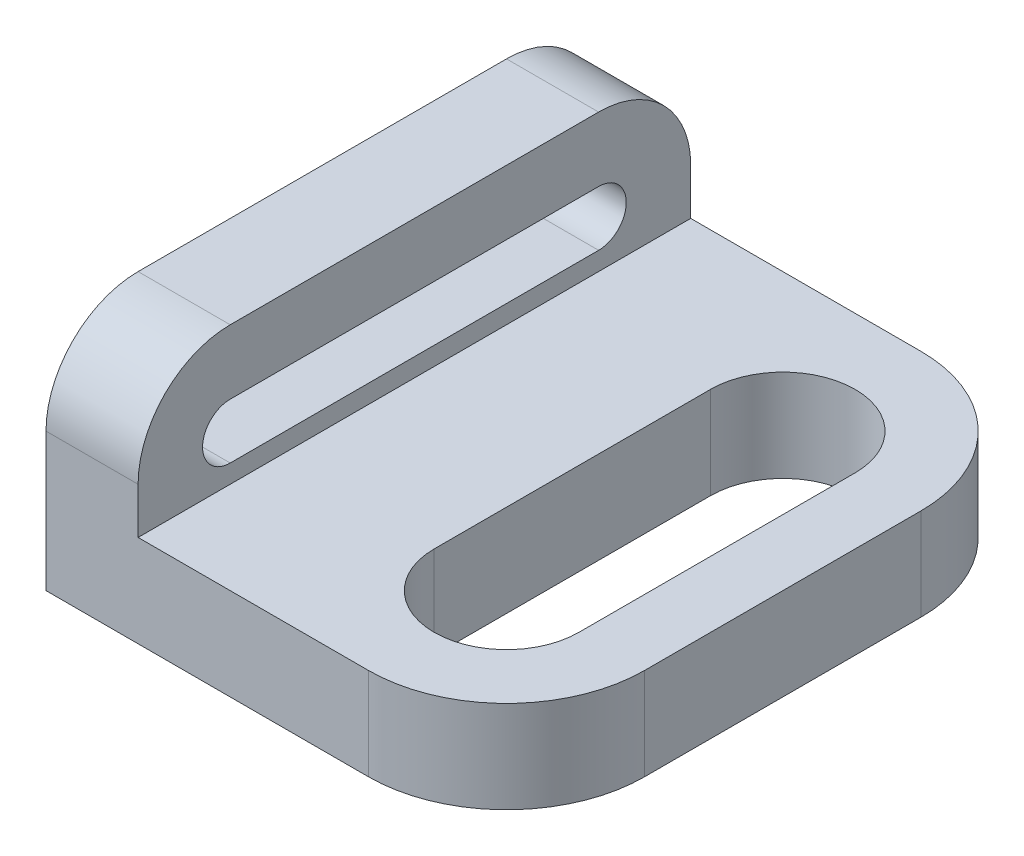
SolidWorks part; units mm, degrees
ref_plane "Ön Düzlem" through (0, 0, 0) normal (0, 0, 1) x (1, 0, 0)
ref_plane "Üst Düzlem" through (0, 0, 0) normal (0, 1, 0) x (1, 0, 0)
ref_plane "Sağ Düzlem" through (0, 0, 0) normal (1, 0, 0) x (0, 0, -1)
sketch "Çizim2" plane through (0, 0, 0) normal (0, 1, 0) x (1, 0, 0)
  line L0 (5.9813, 11.215) -> (5.9813, -48.785) construction
  line L1 (-64.0187, 41.215) -> (35.9813, 41.215)
  line L2 (-64.0187, 41.215) -> (-64.0187, -78.785)
  line L3 (-64.0187, -78.785) -> (35.9813, -78.785)
  line L4 (35.9813, 41.215) -> (35.9813, -78.785)
  line L5 (21.6822, 11.215) -> (21.6822, -48.785)
  line L6 (-9.7196, 11.215) -> (-9.7196, -48.785)
  line L7 (-44.0187, 41.215) -> (-44.0187, -78.785)
  arc A0 (21.6822, 11.215) -> (-9.7196, 11.215) centre (5.9813, 11.215) ccw
  arc A1 (-9.7196, -48.785) -> (21.6822, -48.785) centre (5.9813, -48.785) ccw
  point P6 (5.9813, -18.785)
  dimension "D1" = 120
  dimension "D2" = 100
  dimension "D3" = 60
  dimension "D4" = 70
  dimension "D5" = 30
  dimension "D6" = 20
extrude "Yükseklik-Ekstrüzyon3" add sketch "Çizim2" along normal blind 20 contours L1 L7 L3 L4 A1 L6 A0 L5 | L7 L1 L2 L3
fillet "Radyus1" radius 30 2 edges at (35.9813, 10, -41.215) (35.9813, 10, 78.785)
sketch "Çizim3" plane through (0, 0, 0) normal (0, 1, 0) x (1, 0, 0)
  line L0 (-44.0187, 41.215) -> (-44.0187, -78.785)
  line L1 (-64.0187, 41.215) -> (5.9813, 41.215) construction
  line L2 (-64.0187, -78.785) -> (5.9813, -78.785) construction
  dimension "D1" = 20
extrude "Ekstrüzyon-İnce1" add sketch "Çizim3" along normal blind 50 thin
fillet "Radyus2" radius 20 2 edges at (-54.0187, 50, 78.785) (-54.0187, 50, -41.215)
sketch "Çizim6" plane through (-44.0187, 0, 0) normal (1, 0, 0) x (0, 0, -1)
  line L0 (-58.785, 30) -> (21.215, 30) construction
  line L1 (-58.785, 36) -> (21.215, 36)
  line L2 (-58.785, 24) -> (21.215, 24)
  arc A0 (-58.785, 36) -> (-58.785, 24) centre (-58.785, 30) ccw
  arc A1 (21.215, 24) -> (21.215, 36) centre (21.215, 30) ccw
  point P2 (-18.785, 30)
  point P7 (0, 0)
  point P8 (0, 0)
  point P9 (-58.2823, 34.2161)
  dimension "D4" = 6
  dimension "D1" = 80
  dimension "D2" = 20
  dimension "D3" = 30
extrude "Kes-Ekstrüzyon3" cut sketch "Çizim6" against normal blind 20 contours L2 A1 L1 A0
